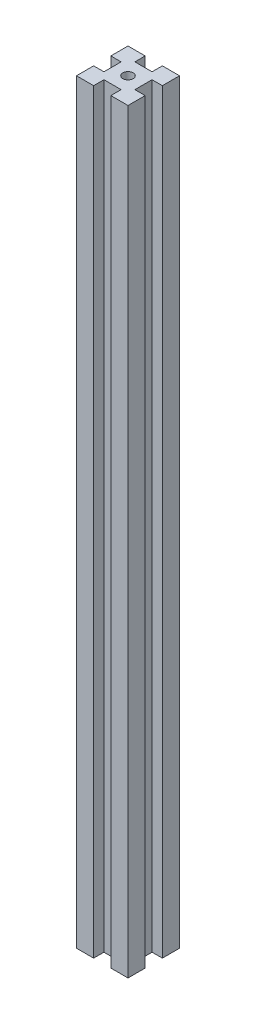
SolidWorks part; units mm, degrees
ref_plane "Front Plane" through (0, 0, 0) normal (0, 0, 1) x (1, 0, 0)
ref_plane "Top Plane" through (0, 0, 0) normal (0, 1, 0) x (1, 0, 0)
ref_plane "Right Plane" through (0, 0, 0) normal (1, 0, 0) x (0, 0, -1)
sketch "Sketch1" plane through (0, 0, 0) normal (0, 1, 0) x (1, 0, 0)
  line L0 (0, 0) -> (0, 4.5) construction
  line L1 (-7.5, -7.5) -> (-2.5, -7.5)
  line L2 (-7.5, -7.5) -> (-7.5, -2.5)
  line L3 (-7.5, 7.5) -> (-2.5, 7.5)
  line L4 (7.5, -7.5) -> (7.5, -2.5)
  line L5 (-7.5, -7.5) -> (7.5, 7.5) construction
  line L6 (-7.5, 7.5) -> (7.5, -7.5) construction
  line L7 (0, 12.4954) -> (0, 7.5) construction
  line L8 (0, -13.7014) -> (0, -7.5) construction
  line L9 (0, 0) -> (-7.5, 0) construction
  line L10 (-7.5, 0) -> (4.5, 0) construction
  line L11 (-7.5, 2.5) -> (-4.5, 2.5)
  line L12 (-4.5, 2.5) -> (-4.5, -2.5)
  line L13 (-4.5, -2.5) -> (-7.5, -2.5)
  line L14 (-7.5, 2.5) -> (-7.5, 7.5)
  line L15 (4.5, -2.5) -> (7.5, -2.5)
  line L16 (7.5, 2.5) -> (4.5, 2.5)
  line L17 (4.5, 2.5) -> (4.5, -2.5)
  line L18 (7.5, 2.5) -> (7.5, 7.5)
  line L19 (7.5, 0) -> (17.7081, 0) construction
  line L20 (-2.5, 7.5) -> (-2.5, 4.5)
  line L21 (-2.5, 4.5) -> (2.5, 4.5)
  line L22 (2.5, 4.5) -> (2.5, 7.5)
  line L23 (2.5, -4.5) -> (2.5, -7.5)
  line L24 (-2.5, -7.5) -> (-2.5, -4.5)
  line L25 (-2.5, -4.5) -> (2.5, -4.5)
  line L26 (2.5, 7.5) -> (7.5, 7.5)
  line L27 (0, 7.5) -> (0, 12.4954) construction
  line L28 (0, 4.5) -> (0, -4.5) construction
  line L29 (2.5, -7.5) -> (7.5, -7.5)
  line L30 (0, -7.5) -> (0, -13.7014) construction
  line L31 (0, -4.5) -> (0, 0) construction
  circle A0 centre (0, 0) radius 1.5
  point P0 (0, 0)
  dimension "D1" = 15
  dimension "D2" = 15
  dimension "D3" = 5
  dimension "D4" = 5
  dimension "D5" = 3
  dimension "D6" = 5
  dimension "D7" = 5
  dimension "D8" = 3
extrude "Boss-Extrude1" add sketch "Sketch1" along normal blind 220
